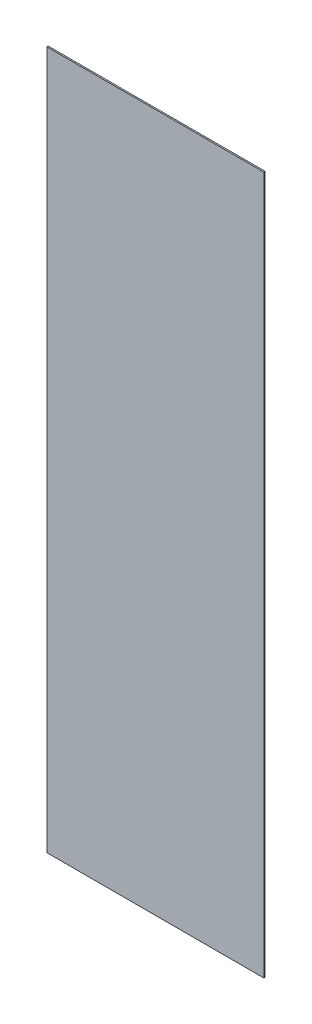
SolidWorks part; units mm, degrees
ref_plane "Alzado" through (0, 0, 0) normal (0, 0, 1) x (1, 0, 0)
ref_plane "Planta" through (0, 0, 0) normal (0, 1, 0) x (1, 0, 0)
ref_plane "Vista lateral" through (0, 0, 0) normal (1, 0, 0) x (0, 0, -1)
sketch "Croquis1" plane through (0, 0, 0) normal (0, 0, 1) x (1, 0, 0)
  line L1 (1580, 5080) -> (-1580, 5080)
  line L2 (1580, 5080) -> (1580, -5080)
  line L3 (1580, -5080) -> (-1580, -5080)
  line L4 (-1580, 5080) -> (-1580, -5080)
  line L5 (1580, 5080) -> (-1580, -5080) construction
  line L6 (1580, -5080) -> (-1580, 5080) construction
  point P0 (0, 0)
extrude "Saliente-Extruir1" add sketch "Croquis1" along normal blind 20
